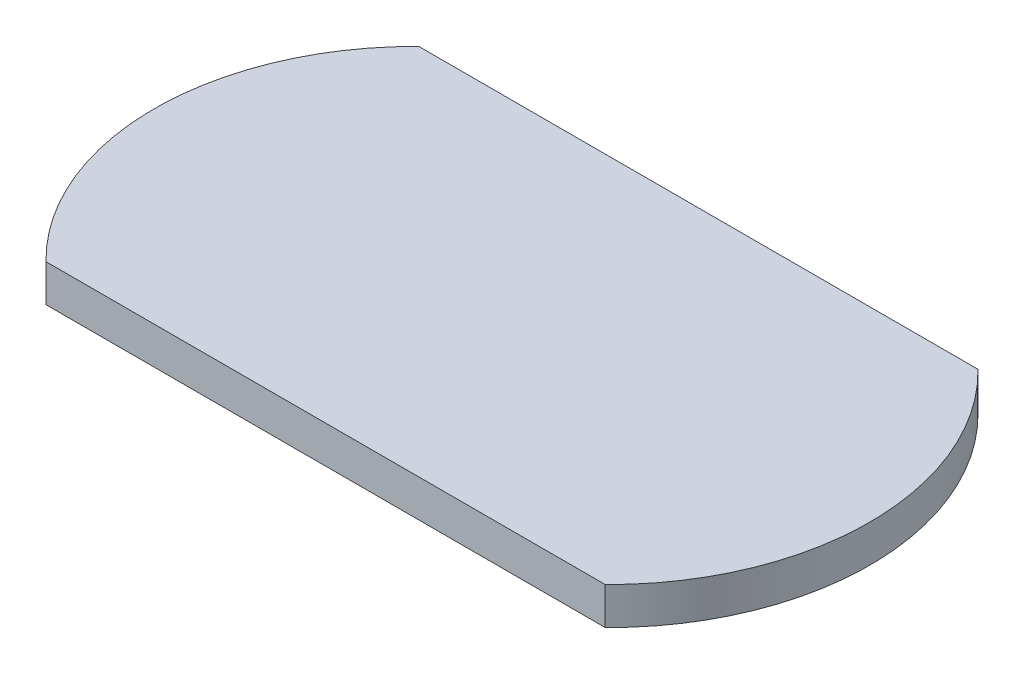
SolidWorks part; units mm, degrees
ref_plane "Front Plane" through (0, 0, 0) normal (0, 0, 1) x (1, 0, 0)
ref_plane "Top Plane" through (0, 0, 0) normal (0, 1, 0) x (1, 0, 0)
ref_plane "Right Plane" through (0, 0, 0) normal (1, 0, 0) x (0, 0, -1)
sketch "Sketch1" plane through (0, 0, 0) normal (0, 1, 0) x (1, 0, 0)
  line L1 (-10.2809, 5.5506) -> (4.7191, 5.5506)
  line L2 (-10.2809, 5.5506) -> (-10.2809, -4.4494)
  line L3 (-10.2809, -4.4494) -> (4.7191, -4.4494)
  line L4 (4.7191, 5.5506) -> (4.7191, -4.4494)
  arc A0 (-10.2809, 5.5506) -> (-10.2809, -4.4494) centre (-5.382, 0.5506) ccw
  arc A1 (4.7191, 5.5506) -> (4.7191, -4.4494) centre (-0.1799, 0.5506) cw
  point P10 (-7.4406, 7.0646)
  point P11 (-7.3615, -3.0277)
  point P12 (0, 0)
  point P13 (0, 0)
  point P14 (0, 0)
  point P15 (-6.4114, -2.7108)
  point P16 (-10.7849, 1.9777)
  point P17 (4.7186, -4.4494)
  point P18 (4.7186, -4.4494)
  point P19 (4.7185, -4.449)
  point P20 (0, 0)
  dimension "D3" = 0
  dimension "D7" = 0
  dimension "D1" = 15
  dimension "D4" = 0
  dimension "D5" = 0
  dimension "D6" = 0
  dimension "D8" = 0
  dimension "D9" = 0
  dimension "D10" = 0
extrude "Boss-Extrude1" add sketch "Sketch1" along normal blind 1 contours L2 A0 | L4 L1 L2 L3 | A1 L4
